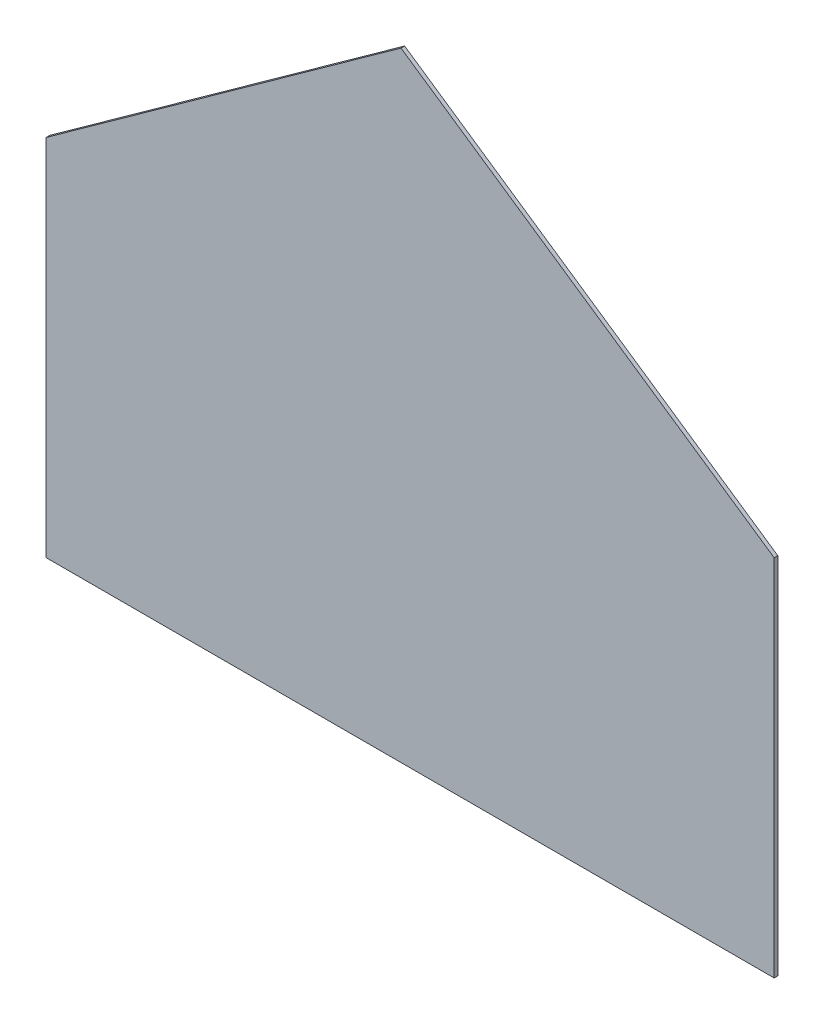
SolidWorks part; units mm, degrees
ref_plane "Front Plane" through (0, 0, 0) normal (0, 0, 1) x (1, 0, 0)
ref_plane "Top Plane" through (0, 0, 0) normal (0, 1, 0) x (1, 0, 0)
ref_plane "Right Plane" through (0, 0, 0) normal (1, 0, 0) x (0, 0, -1)
sketch "Sketch1" plane through (0, 0, 0) normal (0, 0, 1) x (1, 0, 0)
  line L0 (-254, 0) -> (254, 0)
  line L1 (-254, 0) -> (-254, 254)
  line L2 (0, 152.2531) -> (0, -125.2365) construction
  line L3 (254, 0) -> (254, 254)
  line L4 (-254, 254) -> (-6.4146, 431.7766)
  line L5 (-6.4146, 431.7766) -> (254, 254)
  point P3 (0, 0)
  point P8 (0, 0)
  point P10 (0, 0)
  point P11 (0, 0)
  point P12 (0, 508.5542)
  dimension "D1" = 508
  dimension "D2" = 304.8
  dimension "D3" = 110
  dimension "D4" = 254
extrude "Boss-Extrude1" add sketch "Sketch1" along normal mid plane 2.54
